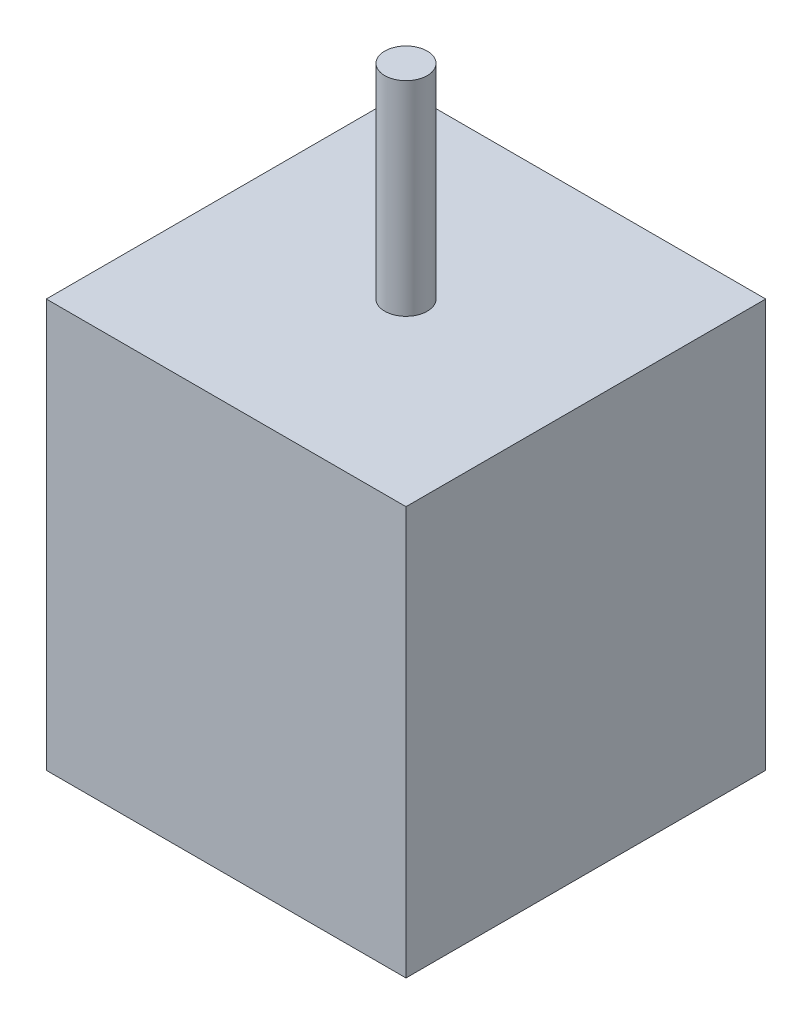
SolidWorks part; units mm, degrees
ref_plane "Front Plane" through (0, 0, 0) normal (0, 0, 1) x (1, 0, 0)
ref_plane "Top Plane" through (0, 0, 0) normal (0, 1, 0) x (1, 0, 0)
ref_plane "Right Plane" through (0, 0, 0) normal (1, 0, 0) x (0, 0, -1)
sketch "Sketch1" plane through (0, 0, 0) normal (0, 1, 0) x (1, 0, 0)
  line L1 (-21.15, -21.15) -> (21.15, -21.15)
  line L2 (-21.15, -21.15) -> (-21.15, 21.15)
  line L3 (-21.15, 21.15) -> (21.15, 21.15)
  line L4 (21.15, -21.15) -> (21.15, 21.15)
  line L5 (-21.15, -21.15) -> (21.15, 21.15) construction
  line L6 (-21.15, 21.15) -> (21.15, -21.15) construction
  point P0 (0, 0)
  dimension "D1" = 42.3
sketch "Sketch2" plane through (0, 0, 0) normal (0, 1, 0) x (1, 0, 0)
  circle A0 centre (0, 0) radius 2.5
  dimension "D1" = 5
extrude "Boss-Extrude1" add sketch "Sketch2" along normal blind 24
extrude "Boss-Extrude2" add sketch "Sketch1" against normal blind 48
